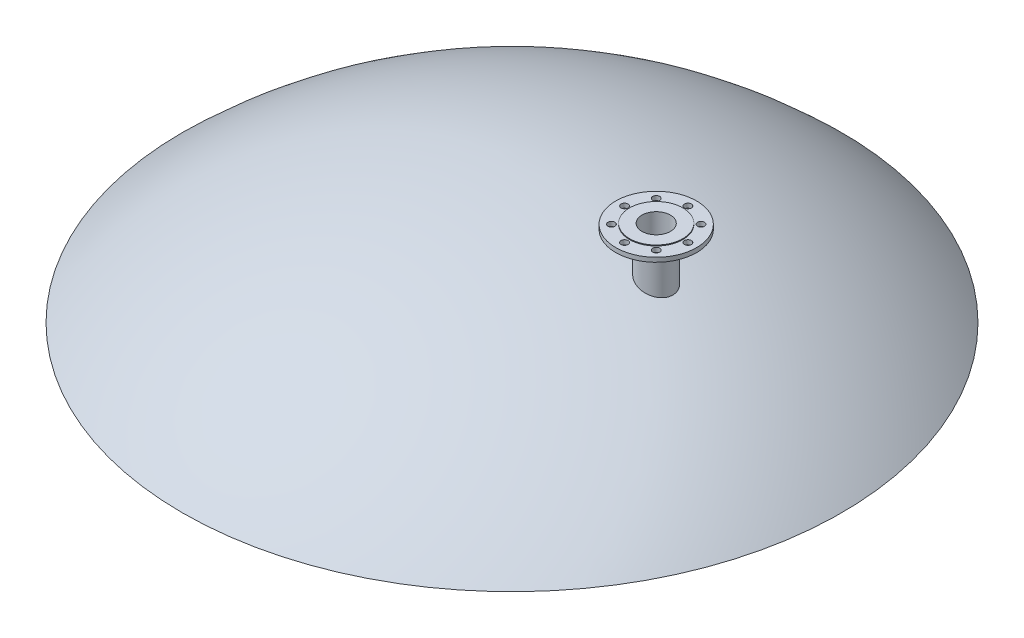
SolidWorks part; units mm, degrees
ref_plane "Ön Düzlem" through (0, 0, 0) normal (0, 0, 1) x (1, 0, 0)
ref_plane "Üst Düzlem" through (0, 0, 0) normal (0, 1, 0) x (1, 0, 0)
ref_plane "Sağ Düzlem" through (0, 0, 0) normal (1, 0, 0) x (0, 0, -1)
sketch "Çizim1" plane through (0, 0, 0) normal (0, 0, 1) x (1, 0, 0)
  line L0 (0, 399.2185) -> (0, -458.4706) construction
  line L1 (-754, 0) -> (870.871, 0) construction
  line L2 (-754, 0) -> (-750, 0)
  line L3 (0, 300) -> (0, 302.7625)
  arc A1 (0, 300) -> (-750, 0) centre (0, -787.5) ccw
  arc A2 (0, 302.7625) -> (-754, 0) centre (0, -787.5) ccw
  point P5 (0, 300)
  point P7 (0, 300)
  point P11 (-750, 0)
  point P12 (750, 0)
  dimension "D1" = 300
  dimension "D2" = 1500
  dimension "D3" = 750
  dimension "D4" = 4
revolve "Döndür1" add sketch "Çizim1" angle 360 about L0
sketch "Çizim4" plane through (0, 0, 0) normal (0, -1, 0) x (1, 0, 0)
  circle A0 centre (0, 0) radius 750
  dimension "D1" = 1500
extrude "Kes-Ekstrüzyon1" cut sketch "Çizim4" against normal blind 1
ref_plane "Düzlem1" through (0, 255, 0) normal (0, 1, 0) x (1, 0, 0)
sketch "Çizim5" plane through (0, 255, 0) normal (0, 1, 0) x (1, 0, 0)
  circle A0 centre (0, 0) radius 34
  circle A1 centre (0, 0) radius 44
  dimension "D1" = 68
  dimension "D2" = 88
extrude "Yükseklik-Ekstrüzyon4" add sketch "Çizim5" along normal up to next separate body
ref_plane "Düzlem2" through (0, 300, 0) normal (0, 1, 0) x (1, 0, 0)
sketch "Çizim7" plane through (0, 300, 0) normal (0, 1, 0) x (1, 0, 0)
  circle A0 centre (330, 0) radius 32.5
  circle A1 centre (330, 0) radius 38.05
  dimension "D1" = 65
  dimension "D2" = 76.1
  dimension "D3" = 330
extrude "Yükseklik-Ekstrüzyon6" add sketch "Çizim7" along normal blind 50 and the other way up to next
sketch "Çizim8" plane through (0, 350, 0) normal (0, 1, 0) x (1, 0, 0)
  circle A0 centre (330, 0) radius 32.5
  dimension "D1" = 65
extrude "Kes-Ekstrüzyon3" cut sketch "Çizim8" against normal up to next
sketch "Çizim9" plane through (0, 350, 0) normal (0, 1, 0) x (1, 0, 0)
  circle A0 centre (330, 0) radius 32.5
  circle A1 centre (330, 0) radius 92.5
  dimension "D1" = 65
  dimension "D2" = 185
extrude "Yükseklik-Ekstrüzyon7" add sketch "Çizim9" along normal blind 10
sketch "Çizim10" plane through (0, 360, 0) normal (0, 1, 0) x (1, 0, 0)
  circle A0 centre (330, 0) radius 32.5
  circle A1 centre (330, 0) radius 61
  dimension "D1" = 65
  dimension "D2" = 122
extrude "Yükseklik-Ekstrüzyon8" add sketch "Çizim10" along normal blind 2
sketch "Çizim13" plane through (0, 360, 0) normal (0, 1, 0) x (1, 0, 0)
  line L0 (237.5, 0) -> (422.5, 0) construction
  line L1 (330, -92.5) -> (330, 92.5) construction
  circle A0 centre (330, 0) radius 92.5 construction
  circle A1 centre (257.5, 0) radius 8
  circle A3 centre (278.7348, 51.2652) radius 8
  circle A4 centre (330, 72.5) radius 8
  circle A5 centre (381.2652, 51.2652) radius 8
  circle A6 centre (402.5, 0) radius 8
  circle A7 centre (381.2652, -51.2652) radius 8
  circle A8 centre (330, -72.5) radius 8
  circle A9 centre (278.7348, -51.2652) radius 8
  point P9 (330, 0)
  point P11 (0, 0)
  dimension "D1" = 16
  dimension "D2" = 72.5
  dimension "D4" = 72.5
  dimension "D3" = 8
extrude "Kes-Ekstrüzyon4" cut sketch "Çizim13" against normal blind 20
